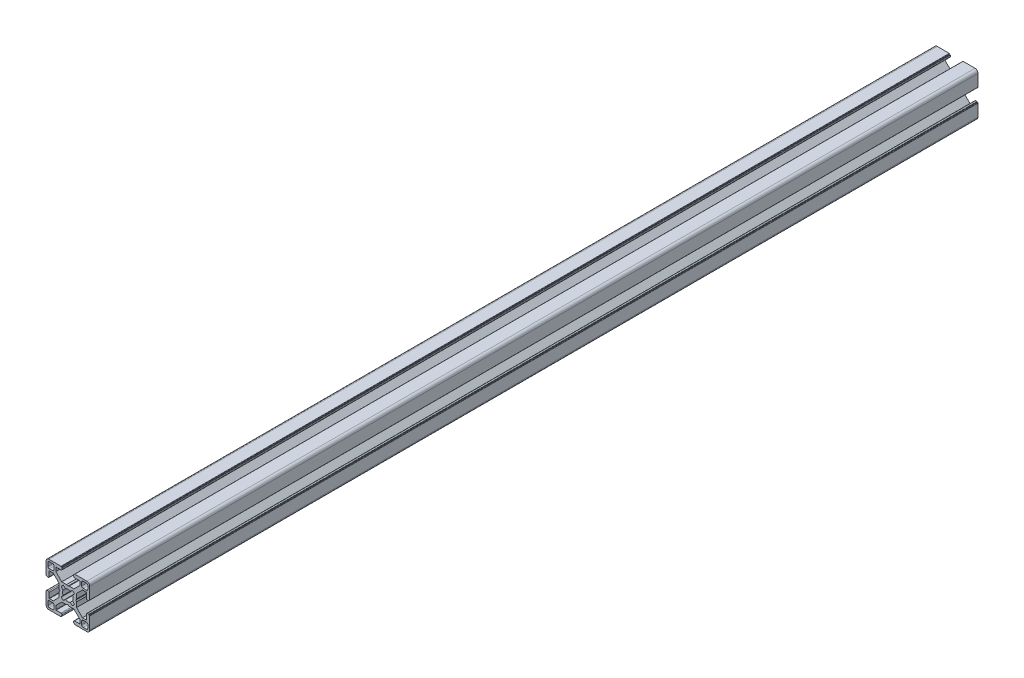
SolidWorks part; units mm, degrees
material "1060 Alloy"
ref_plane "Front" through (0, 0, 0) normal (0, 0, 1) x (1, 0, 0)
ref_plane "Top" through (0, 0, 0) normal (0, 1, 0) x (1, 0, 0)
ref_plane "Right" through (0, 0, 0) normal (1, 0, 0) x (0, 0, -1)
ref_plane "Plane1" through (0, 0, 25) normal (0, 0, 1) x (1, 0, 0)
sketch "Sketch1" plane through (0, 0, 25) normal (0, 0, 1) x (1, 0, 0)
  line L0 (-12.7, 13.7) -> (-10.5, 13.7)
  line L1 (-9.5, 12.7) -> (-9.5, 10.5)
  line L2 (-10.5, 9.5) -> (-12.7, 9.5)
  line L3 (-13.7, 10.5) -> (-13.7, 12.7)
  line L4 (-10.5, -13.7) -> (-12.7, -13.7)
  line L5 (-13.7, -12.7) -> (-13.7, -10.5)
  line L6 (-12.7, -9.5) -> (-10.5, -9.5)
  line L7 (-9.5, -10.5) -> (-9.5, -12.7)
  line L8 (10.5, 13.7) -> (12.7, 13.7)
  line L9 (13.7, 12.7) -> (13.7, 10.5)
  line L10 (12.7, 9.5) -> (10.5, 9.5)
  line L11 (9.5, 10.5) -> (9.5, 12.7)
  line L12 (13.7, -10.5) -> (13.7, -12.7)
  line L13 (12.7, -13.7) -> (10.5, -13.7)
  line L14 (9.5, -12.7) -> (9.5, -10.5)
  line L15 (10.5, -9.5) -> (12.7, -9.5)
  line L16 (-3.1359, 4.5184) -> (-1.6001, 3.2806)
  line L17 (1.6001, 3.2806) -> (3.1359, 4.5184)
  line L18 (4.5053, 3.1547) -> (3.2806, 1.6001)
  line L19 (3.2806, -1.6001) -> (4.5053, -3.1547)
  line L20 (3.1359, -4.5184) -> (1.6001, -3.2806)
  line L21 (-1.6001, -3.2806) -> (-3.1359, -4.5184)
  line L22 (-4.5053, -3.1547) -> (-3.2806, -1.6001)
  line L23 (-3.2806, 1.6001) -> (-4.5053, 3.1547)
  line L24 (-4.05, 13.4) -> (-4.05, 14.3)
  line L25 (-4.25, 14.5) -> (-4.35, 14.5)
  line L26 (-4.55, 14.7) -> (-4.55, 14.8)
  line L27 (-4.75, 15) -> (-13, 15)
  line L28 (-15, 13) -> (-15, 4.75)
  line L29 (-14.8, 4.55) -> (-14.7, 4.55)
  line L30 (-14.5, 4.35) -> (-14.5, 4.25)
  line L31 (-14.3, 4.05) -> (-13.4, 4.05)
  line L32 (-12.8, 4.65) -> (-12.8, 8.05)
  line L33 (-12.6, 8.25) -> (-10.05, 8.25)
  line L34 (-10.05, 8.25) -> (-6.0045, 4.2045)
  line L35 (-6.0045, 4.2045) -> (-6.0045, 0.9)
  line L36 (-6.0045, 0.9) -> (-5.4849, 0)
  line L37 (-5.4849, 0) -> (-6.0045, -0.9)
  line L38 (-6.0045, -0.9) -> (-6.0045, -4.2045)
  line L39 (-6.0045, -4.2045) -> (-10.05, -8.25)
  line L40 (-10.05, -8.25) -> (-12.6, -8.25)
  line L41 (-12.8, -8.05) -> (-12.8, -4.65)
  line L42 (-13.4, -4.05) -> (-14.3, -4.05)
  line L43 (-14.5, -4.25) -> (-14.5, -4.35)
  line L44 (-14.7, -4.55) -> (-14.8, -4.55)
  line L45 (-15, -4.75) -> (-15, -13)
  line L46 (-13, -15) -> (-4.75, -15)
  line L47 (-4.55, -14.8) -> (-4.55, -14.7)
  line L48 (-4.35, -14.5) -> (-4.25, -14.5)
  line L49 (-4.05, -14.3) -> (-4.05, -13.4)
  line L50 (-4.65, -12.8) -> (-8.05, -12.8)
  line L51 (-8.25, -12.6) -> (-8.25, -10.05)
  line L52 (-8.25, -10.05) -> (-4.2045, -6)
  line L53 (-4.2045, -6) -> (-0.9, -6)
  line L54 (-0.9, -6) -> (0, -5.4849)
  line L55 (0, -5.4849) -> (0.9, -6)
  line L56 (0.9, -6) -> (4.2045, -6)
  line L57 (4.2045, -6) -> (8.25, -10.05)
  line L58 (8.25, -10.05) -> (8.25, -12.6)
  line L59 (8.05, -12.8) -> (4.65, -12.8)
  line L60 (4.05, -13.4) -> (4.05, -14.3)
  line L61 (4.25, -14.5) -> (4.35, -14.5)
  line L62 (4.55, -14.7) -> (4.55, -14.8)
  line L63 (4.75, -15) -> (13, -15)
  line L64 (15, -13) -> (15, -4.75)
  line L65 (14.8, -4.55) -> (14.7, -4.55)
  line L66 (14.5, -4.35) -> (14.5, -4.25)
  line L67 (14.3, -4.05) -> (13.4, -4.05)
  line L68 (12.8, -4.65) -> (12.8, -8.05)
  line L69 (12.6, -8.25) -> (10.05, -8.25)
  line L70 (10.05, -8.25) -> (6.0045, -4.2045)
  line L71 (6.0045, -4.2045) -> (6.0045, -0.9)
  line L72 (6.0045, -0.9) -> (5.4849, 0)
  line L73 (5.4849, 0) -> (6.0045, 0.9)
  line L74 (6.0045, 0.9) -> (6.0045, 4.2045)
  line L75 (6.0045, 4.2045) -> (10.05, 8.25)
  line L76 (10.05, 8.25) -> (12.6, 8.25)
  line L77 (12.8, 8.05) -> (12.8, 4.65)
  line L78 (13.4, 4.05) -> (14.3, 4.05)
  line L79 (14.5, 4.25) -> (14.5, 4.35)
  line L80 (14.7, 4.55) -> (14.8, 4.55)
  line L81 (15, 4.75) -> (15, 13)
  line L82 (13, 15) -> (4.75, 15)
  line L83 (4.55, 14.8) -> (4.55, 14.7)
  line L84 (4.35, 14.5) -> (4.25, 14.5)
  line L85 (4.05, 14.3) -> (4.05, 13.4)
  line L86 (4.65, 12.8) -> (8.05, 12.8)
  line L87 (8.25, 12.6) -> (8.25, 10.05)
  line L88 (8.25, 10.05) -> (4.2045, 6)
  line L89 (4.2045, 6) -> (0.9, 6)
  line L90 (0.9, 6) -> (0, 5.4849)
  line L91 (0, 5.4849) -> (-0.9, 6)
  line L92 (-0.9, 6) -> (-4.2045, 6)
  line L93 (-4.2045, 6) -> (-8.25, 10.05)
  line L94 (-8.25, 10.05) -> (-8.25, 12.6)
  line L95 (-8.05, 12.8) -> (-4.65, 12.8)
  arc A0 (-13.7, 12.7) -> (-12.7, 13.7) centre (-12.7, 12.7) cw
  arc A1 (-10.5, 13.7) -> (-9.5, 12.7) centre (-10.5, 12.7) cw
  arc A2 (-9.5, 10.5) -> (-10.5, 9.5) centre (-10.5, 10.5) cw
  arc A3 (-12.7, 9.5) -> (-13.7, 10.5) centre (-12.7, 10.5) cw
  arc A4 (-9.5, -12.7) -> (-10.5, -13.7) centre (-10.5, -12.7) cw
  arc A5 (-12.7, -13.7) -> (-13.7, -12.7) centre (-12.7, -12.7) cw
  arc A6 (-13.7, -10.5) -> (-12.7, -9.5) centre (-12.7, -10.5) cw
  arc A7 (-10.5, -9.5) -> (-9.5, -10.5) centre (-10.5, -10.5) cw
  arc A8 (9.5, 12.7) -> (10.5, 13.7) centre (10.5, 12.7) cw
  arc A9 (12.7, 13.7) -> (13.7, 12.7) centre (12.7, 12.7) cw
  arc A10 (13.7, 10.5) -> (12.7, 9.5) centre (12.7, 10.5) cw
  arc A11 (10.5, 9.5) -> (9.5, 10.5) centre (10.5, 10.5) cw
  arc A12 (13.7, -12.7) -> (12.7, -13.7) centre (12.7, -12.7) cw
  arc A13 (10.5, -13.7) -> (9.5, -12.7) centre (10.5, -12.7) cw
  arc A14 (9.5, -10.5) -> (10.5, -9.5) centre (10.5, -10.5) cw
  arc A15 (12.7, -9.5) -> (13.7, -10.5) centre (12.7, -10.5) cw
  arc A16 (-4.5053, 3.1547) -> (-3.1359, 4.5184) centre (0, 0) cw
  arc A17 (-1.6001, 3.2806) -> (1.6001, 3.2806) centre (0, 0) cw
  arc A18 (3.1359, 4.5184) -> (4.5053, 3.1547) centre (0, 0) cw
  arc A19 (3.2806, 1.6001) -> (3.2806, -1.6001) centre (0, 0) cw
  arc A20 (4.5053, -3.1547) -> (3.1359, -4.5184) centre (0, 0) cw
  arc A21 (1.6001, -3.2806) -> (-1.6001, -3.2806) centre (0, 0) cw
  arc A22 (-3.1359, -4.5184) -> (-4.5053, -3.1547) centre (0, 0) cw
  arc A23 (-3.2806, -1.6001) -> (-3.2806, 1.6001) centre (0, 0) cw
  arc A24 (-4.65, 12.8) -> (-4.05, 13.4) centre (-4.65, 13.4) ccw
  arc A25 (-4.05, 14.3) -> (-4.25, 14.5) centre (-4.25, 14.3) ccw
  arc A26 (-4.35, 14.5) -> (-4.55, 14.7) centre (-4.35, 14.7) cw
  arc A27 (-4.55, 14.8) -> (-4.75, 15) centre (-4.75, 14.8) ccw
  arc A28 (-13, 15) -> (-15, 13) centre (-13, 13) ccw
  arc A29 (-15, 4.75) -> (-14.8, 4.55) centre (-14.8, 4.75) ccw
  arc A30 (-14.7, 4.55) -> (-14.5, 4.35) centre (-14.7, 4.35) cw
  arc A31 (-14.5, 4.25) -> (-14.3, 4.05) centre (-14.3, 4.25) ccw
  arc A32 (-13.4, 4.05) -> (-12.8, 4.65) centre (-13.4, 4.65) ccw
  arc A33 (-12.8, 8.05) -> (-12.6, 8.25) centre (-12.6, 8.05) cw
  arc A34 (-12.6, -8.25) -> (-12.8, -8.05) centre (-12.6, -8.05) cw
  arc A35 (-12.8, -4.65) -> (-13.4, -4.05) centre (-13.4, -4.65) ccw
  arc A36 (-14.3, -4.05) -> (-14.5, -4.25) centre (-14.3, -4.25) ccw
  arc A37 (-14.5, -4.35) -> (-14.7, -4.55) centre (-14.7, -4.35) cw
  arc A38 (-14.8, -4.55) -> (-15, -4.75) centre (-14.8, -4.75) ccw
  arc A39 (-15, -13) -> (-13, -15) centre (-13, -13) ccw
  arc A40 (-4.75, -15) -> (-4.55, -14.8) centre (-4.75, -14.8) ccw
  arc A41 (-4.55, -14.7) -> (-4.35, -14.5) centre (-4.35, -14.7) cw
  arc A42 (-4.25, -14.5) -> (-4.05, -14.3) centre (-4.25, -14.3) ccw
  arc A43 (-4.05, -13.4) -> (-4.65, -12.8) centre (-4.65, -13.4) ccw
  arc A44 (-8.05, -12.8) -> (-8.25, -12.6) centre (-8.05, -12.6) cw
  arc A45 (8.25, -12.6) -> (8.05, -12.8) centre (8.05, -12.6) cw
  arc A46 (4.65, -12.8) -> (4.05, -13.4) centre (4.65, -13.4) ccw
  arc A47 (4.05, -14.3) -> (4.25, -14.5) centre (4.25, -14.3) ccw
  arc A48 (4.35, -14.5) -> (4.55, -14.7) centre (4.35, -14.7) cw
  arc A49 (4.55, -14.8) -> (4.75, -15) centre (4.75, -14.8) ccw
  arc A50 (13, -15) -> (15, -13) centre (13, -13) ccw
  arc A51 (15, -4.75) -> (14.8, -4.55) centre (14.8, -4.75) ccw
  arc A52 (14.7, -4.55) -> (14.5, -4.35) centre (14.7, -4.35) cw
  arc A53 (14.5, -4.25) -> (14.3, -4.05) centre (14.3, -4.25) ccw
  arc A54 (13.4, -4.05) -> (12.8, -4.65) centre (13.4, -4.65) ccw
  arc A55 (12.8, -8.05) -> (12.6, -8.25) centre (12.6, -8.05) cw
  arc A56 (12.6, 8.25) -> (12.8, 8.05) centre (12.6, 8.05) cw
  arc A57 (12.8, 4.65) -> (13.4, 4.05) centre (13.4, 4.65) ccw
  arc A58 (14.3, 4.05) -> (14.5, 4.25) centre (14.3, 4.25) ccw
  arc A59 (14.5, 4.35) -> (14.7, 4.55) centre (14.7, 4.35) cw
  arc A60 (14.8, 4.55) -> (15, 4.75) centre (14.8, 4.75) ccw
  arc A61 (15, 13) -> (13, 15) centre (13, 13) ccw
  arc A62 (4.75, 15) -> (4.55, 14.8) centre (4.75, 14.8) ccw
  arc A63 (4.55, 14.7) -> (4.35, 14.5) centre (4.35, 14.7) cw
  arc A64 (4.25, 14.5) -> (4.05, 14.3) centre (4.25, 14.3) ccw
  arc A65 (4.05, 13.4) -> (4.65, 12.8) centre (4.65, 13.4) ccw
  arc A66 (8.05, 12.8) -> (8.25, 12.6) centre (8.05, 12.6) cw
  arc A67 (-8.25, 12.6) -> (-8.05, 12.8) centre (-8.05, 12.6) cw
extrude "Boss-Extrude1" add sketch "Sketch1" against normal blind 610
